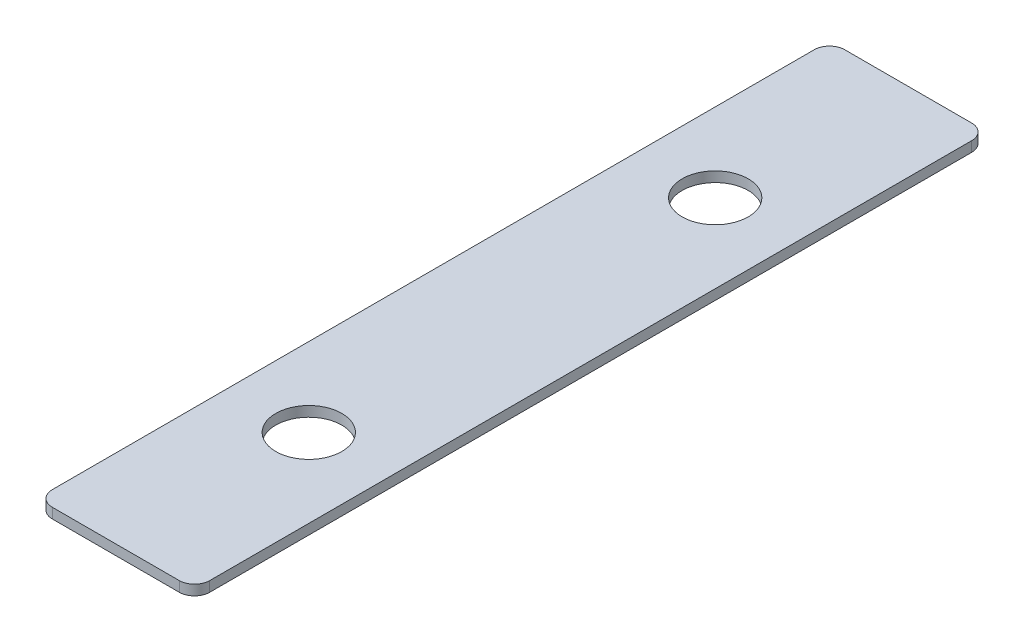
SolidWorks part; units mm, degrees
material "Galvanized Steel"
ref_plane "Front Plane" through (0, 0, 0) normal (0, 0, 1) x (1, 0, 0)
ref_plane "Top Plane" through (0, 0, 0) normal (0, 1, 0) x (1, 0, 0)
ref_plane "Right Plane" through (0, 0, 0) normal (1, 0, 0) x (0, 0, -1)
sketch "Sketch1" plane through (0, 0, 0) normal (0, 1, 0) x (1, 0, 0)
  line L0 (-16, -75.5) -> (-16, 74.5)
  line L5 (-13, 77.5) -> (12, 77.5)
  line L6 (15, -75.5) -> (15, 74.5)
  line L7 (-13, -78.5) -> (12, -78.5)
  circle A0 centre (-0.5, 39.5) radius 6.5
  circle A1 centre (-0.5, -40.5) radius 6.5
  arc A2 (-16, -75.5) -> (-13, -78.5) centre (-13, -75.5) ccw
  arc A3 (15, -75.5) -> (12, -78.5) centre (12, -75.5) cw
  arc A4 (12, 77.5) -> (15, 74.5) centre (12, 74.5) cw
  arc A5 (-16, 74.5) -> (-13, 77.5) centre (-13, 74.5) cw
  point P0 (0, 0)
  dimension "D3" = 13
  dimension "D4" = 13
  dimension "D1" = 3
  dimension "D2" = 80
  dimension "D5" = 38
  dimension "D7" = 15.5
  dimension "D6" = 31
  dimension "D8" = 156
extrude "Boss-Extrude1" add sketch "Sketch1" along normal blind 2
